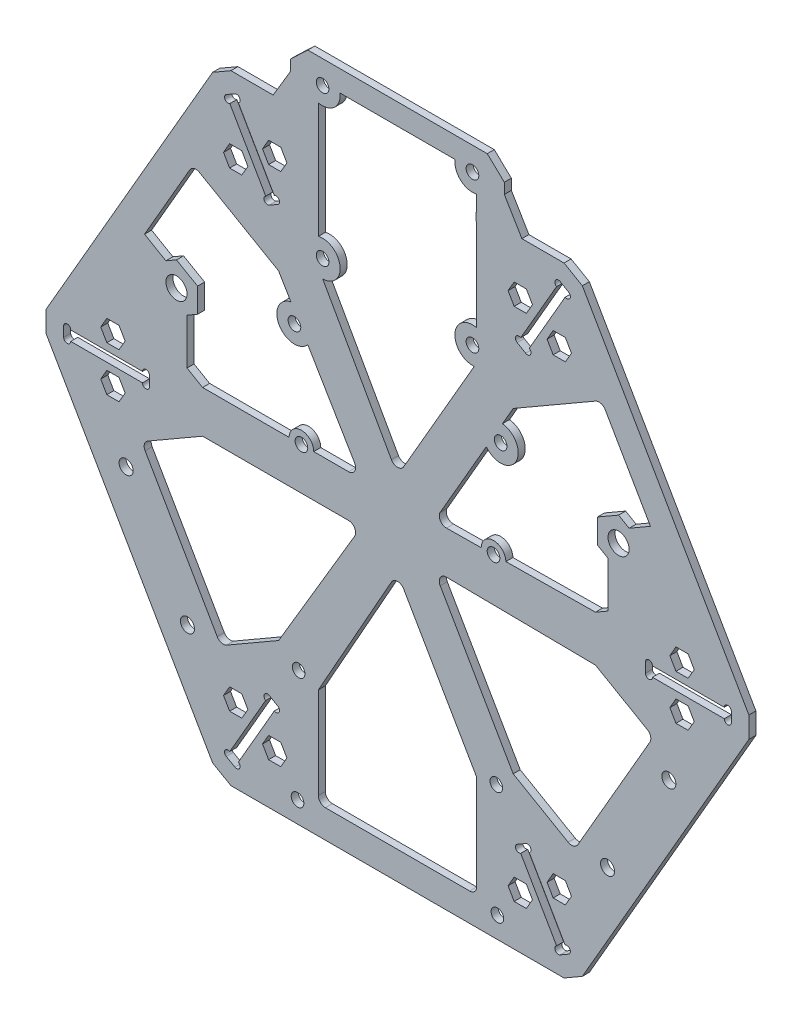
SolidWorks part; units mm, degrees
ref_plane "Alzado" through (0, 0, 0) normal (0, 0, 1) x (1, 0, 0)
ref_plane "Planta" through (0, 0, 0) normal (0, 1, 0) x (1, 0, 0)
ref_plane "Vista lateral" through (0, 0, 0) normal (1, 0, 0) x (0, 0, -1)
sketch "Croquis1" plane through (0, 0, 0) normal (0, 0, 1) x (1, 0, 0)
  line L1 (50.8068, 0) -> (25.4034, 44)
  line L2 (25.4034, 44) -> (-25.4034, 44)
  line L3 (-25.4034, 44) -> (-50.8068, 0)
  line L4 (-50.8068, 0) -> (-25.4034, -44)
  line L5 (-25.4034, -44) -> (25.4034, -44)
  line L6 (25.4034, -44) -> (50.8068, 0)
  circle A0 centre (0, 0) radius 44 construction
extrude "Saliente-Extruir1" add sketch "Croquis1" along normal blind 1
sketch "Croquis2" plane through (0, 0, 1) normal (0, 0, 1) x (1, 0, 0)
  line L0 (-25.4034, -44) -> (25.4034, -44) construction
  line L1 (-11.25, -40) -> (11.25, -40)
  line L2 (0, -44) -> (0, -40) construction
  line L3 (11.25, -40) -> (11.25, -25.4856)
  line L4 (-11.25, -40) -> (-11.25, -26)
  line L5 (0, -40) -> (0, -6) construction
  line L6 (-11.25, -26) -> (0, -6)
  line L7 (0, -6) -> (11.25, -25.4856)
  line L8 (25.4034, -44) -> (50.8068, 0) construction
  line L9 (38.1051, -22) -> (5.1962, -3) construction
  line L10 (29.016, -29.7428) -> (40.266, -10.2572)
  line L11 (29.016, -29.7428) -> (16.4462, -22.4856)
  line L12 (16.4462, -22.4856) -> (5.1962, -3)
  line L13 (5.1962, -3) -> (28.1417, -3.2572)
  line L14 (28.1417, -3.2572) -> (40.266, -10.2572)
  line L15 (-29.016, 29.7428) -> (-40.266, 10.2572)
  line L16 (-40.266, 10.2572) -> (-27.6962, 3)
  line L17 (-29.016, 29.7428) -> (-16.8917, 22.7428)
  line L18 (-16.8917, 22.7428) -> (-5.1962, 3)
  line L19 (-5.1962, 3) -> (-27.6962, 3)
  line L20 (-40.266, -10.2572) -> (-29.016, -29.7428)
  line L21 (-40.266, -10.2572) -> (-27.6962, -3)
  line L22 (-27.6962, -3) -> (-5.1962, -3)
  line L23 (-5.1962, -3) -> (-16.8917, -22.7428)
  line L24 (-16.8917, -22.7428) -> (-29.016, -29.7428)
  line L25 (-25.4034, 44) -> (-50.8068, 0) construction
  line L26 (-38.1051, 22) -> (-34.641, 20) construction
  line L27 (-34.641, 20) -> (-5.1962, 3) construction
  line L28 (-50.8068, 0) -> (-25.4034, -44) construction
  line L29 (-38.1051, -22) -> (-5.1962, -3) construction
  line L30 (40.266, 10.2572) -> (29.016, 29.7428)
  line L31 (29.016, 29.7428) -> (16.4462, 22.4856)
  line L32 (40.266, 10.2572) -> (28.1417, 3.2572)
  line L33 (28.1417, 3.2572) -> (5.1962, 3)
  line L34 (5.1962, 3) -> (16.4462, 22.4856)
  line L35 (11.25, 40) -> (-11.25, 40)
  line L36 (11.25, 40) -> (11.25, 25.4856)
  line L37 (11.25, 25.4856) -> (0, 6)
  line L38 (0, 6) -> (-11.25, 26)
  line L39 (-11.25, 26) -> (-11.25, 40)
  line L40 (50.8068, 0) -> (25.4034, 44) construction
  line L41 (38.1051, 22) -> (34.641, 20) construction
  line L42 (34.641, 20) -> (5.1962, 3) construction
  line L43 (25.4034, 44) -> (-25.4034, 44) construction
  line L44 (0, 44) -> (0, 6) construction
  arc A0 (-11.25, -39) -> (-10.25, -40) centre (-10.25, -39) ccw
  arc A1 (10.25, -40) -> (11.25, -39) centre (10.25, -39) ccw
  arc A2 (0.8773, -7.5196) -> (-0.8603, -7.5293) centre (0.0113, -8.0196) ccw
  arc A3 (6.9507, -3.0197) -> (6.0735, -4.5196) centre (6.9395, -4.0196) ccw
  arc A4 (28.15, -29.2428) -> (29.516, -28.8768) centre (28.65, -28.3768) ccw
  arc A5 (39.766, -11.1232) -> (39.4, -9.7572) centre (38.9, -10.6232) ccw
  arc A6 (-28.15, 29.2428) -> (-29.516, 28.8768) centre (-28.65, 28.3768) ccw
  arc A7 (-39.766, 11.1232) -> (-39.4, 9.7572) centre (-38.9, 10.6232) ccw
  arc A8 (-6.9508, 3) -> (-6.0905, 4.5097) centre (-6.9508, 4) ccw
  arc A9 (-6.0905, -4.5097) -> (-6.9508, -3) centre (-6.9508, -4) ccw
  arc A10 (-39.4, -9.7572) -> (-39.766, -11.1232) centre (-38.9, -10.6232) ccw
  arc A11 (-29.516, -28.8768) -> (-28.15, -29.2428) centre (-28.65, -28.3768) ccw
  arc A12 (39.4, 9.7572) -> (39.766, 11.1232) centre (38.9, 10.6232) ccw
  arc A13 (29.516, 28.8768) -> (28.15, 29.2428) centre (28.65, 28.3768) ccw
  arc A14 (6.0735, 4.5196) -> (6.9507, 3.0197) centre (6.9395, 4.0196) ccw
  arc A15 (-0.8603, 7.5293) -> (0.8773, 7.5196) centre (0.0113, 8.0196) ccw
  arc A16 (11.25, 39) -> (10.25, 40) centre (10.25, 39) ccw
  arc A17 (-10.25, 40) -> (-11.25, 39) centre (-10.25, 39) ccw
  point P7 (0, -40)
  point P20 (34.641, -20)
  point P47 (-34.641, 20)
  point P57 (-34.641, -20)
  point P83 (34.641, 20)
  point P93 (0, 40)
  point P114 (0, 0)
  dimension "D9" = 2
  dimension "D10" = 2
  dimension "D11" = 2
  dimension "D12" = 2
  dimension "D13" = 2
  dimension "D14" = 2
  dimension "D1" = 22.5
  dimension "D2" = 4
  dimension "D3" = 6
  dimension "D4" = 14
  dimension "D5" = 22.5
  dimension "D6" = 4
  dimension "D7" = 6
  dimension "D8" = 14
  dimension "D15" = 3
extrude "Cortar-Extruir2" cut sketch "Croquis2" against normal blind 1 contours L20 A11 L24 L23 A9 L22 L21 A10 | L7 A2 L6 L4 A0 L1 A1 L3 | L10 A5 L14 L13 A3 L12 L11 A4 | L34 A14 L33 L32 A12 L30 A13 L31 | L35 A17 L39 L38 A15 L37 L36 A16 | L19 A8 L18 L17 A6 L15 A7 L16
sketch "Croquis3" plane through (0, 0, 1) normal (0, 0, 1) x (1, 0, 0)
  line L0 (49.9408, -1.5) -> (49.9408, 1.5)
  line L1 (25.4034, -44) -> (50.8068, 0) construction
  line L2 (50.8068, 0) -> (25.4034, 44) construction
  line L3 (49.9408, 1.5) -> (51.6379, 1.5)
  line L4 (51.6379, 1.5) -> (51.6379, -1.5)
  line L5 (51.6379, -1.5) -> (49.9408, -1.5)
  line L6 (23.6714, -44) -> (26.2694, -42.5)
  line L7 (26.2694, -42.5) -> (27.118, -43.9697)
  line L8 (27.118, -43.9697) -> (24.5199, -45.4697)
  line L9 (24.5199, -45.4697) -> (23.6714, -44)
  line L10 (-26.2694, -42.5) -> (-23.6714, -44)
  line L11 (-23.6714, -44) -> (-24.5199, -45.4697)
  line L12 (-24.5199, -45.4697) -> (-27.118, -43.9697)
  line L13 (-27.118, -43.9697) -> (-26.2694, -42.5)
  line L14 (-49.9408, 1.5) -> (-49.9408, -1.5)
  line L15 (-49.9408, -1.5) -> (-51.6379, -1.5)
  line L16 (-51.6379, -1.5) -> (-51.6379, 1.5)
  line L17 (-51.6379, 1.5) -> (-49.9408, 1.5)
  line L18 (-23.6714, 44) -> (-26.2694, 42.5)
  line L19 (-26.2694, 42.5) -> (-27.118, 43.9697)
  line L20 (-27.118, 43.9697) -> (-24.5199, 45.4697)
  line L21 (-24.5199, 45.4697) -> (-23.6714, 44)
  line L22 (26.2694, 42.5) -> (23.6714, 44)
  line L23 (23.6714, 44) -> (24.5199, 45.4697)
  line L24 (24.5199, 45.4697) -> (27.118, 43.9697)
  line L25 (27.118, 43.9697) -> (26.2694, 42.5)
  point P31 (0, 0)
  dimension "D1" = 3
  dimension "D2" = 6
extrude "Cortar-Extruir3" cut sketch "Croquis3" against normal blind 1
sketch "Croquis4" plane through (0, 0, 1) normal (0, 0, 1) x (1, 0, 0)
  line L0 (23.7204, -41.0849) -> (17.6204, -30.5194) construction
  line L1 (24.9704, -43.25) -> (23.7204, -41.0849) construction
  line L2 (26.2694, -42.5) -> (23.6714, -44) construction
  line L3 (17.0142, -30.8694) -> (18.2266, -30.1694)
  line L4 (23.1142, -41.4349) -> (24.3266, -40.7349)
  line L5 (17.5142, -31.7355) -> (22.6142, -40.5689)
  line L6 (23.8266, -39.8689) -> (18.7266, -31.0355)
  line L7 (23.6714, -44) -> (24.9704, -43.25) construction
  line L8 (24.9704, -43.25) -> (26.2694, -42.5) construction
  line L9 (-18.2266, -30.1694) -> (-17.0142, -30.8694)
  line L10 (-24.3266, -40.7349) -> (-23.1142, -41.4349)
  line L11 (-18.7266, -31.0355) -> (-23.8266, -39.8689)
  line L12 (-22.6142, -40.5689) -> (-17.5142, -31.7355)
  line L13 (-23.7204, -41.0849) -> (-17.6204, -30.5194) construction
  line L14 (-24.9704, -43.25) -> (-23.7204, -41.0849) construction
  line L15 (-26.2694, -42.5) -> (-24.9704, -43.25) construction
  line L16 (-24.9704, -43.25) -> (-23.6714, -44) construction
  line L17 (-35.2408, 0.7) -> (-35.2408, -0.7)
  line L18 (-47.4408, 0.7) -> (-47.4408, -0.7)
  line L19 (-36.2408, 0.7) -> (-46.4408, 0.7)
  line L20 (-46.4408, -0.7) -> (-36.2408, -0.7)
  line L21 (-47.4408, 0) -> (-35.2408, 0) construction
  line L22 (-49.9408, 0) -> (-47.4408, 0) construction
  line L23 (-49.9408, 1.5) -> (-49.9408, 0) construction
  line L24 (-49.9408, 0) -> (-49.9408, -1.5) construction
  line L25 (-17.0142, 30.8694) -> (-18.2266, 30.1694)
  line L26 (-23.1142, 41.4349) -> (-24.3266, 40.7349)
  line L27 (-17.5142, 31.7355) -> (-22.6142, 40.5689)
  line L28 (-23.8266, 39.8689) -> (-18.7266, 31.0355)
  line L29 (-23.7204, 41.0849) -> (-17.6204, 30.5194) construction
  line L30 (-24.9704, 43.25) -> (-23.7204, 41.0849) construction
  line L31 (-23.6714, 44) -> (-24.9704, 43.25) construction
  line L32 (-24.9704, 43.25) -> (-26.2694, 42.5) construction
  line L33 (18.2266, 30.1694) -> (17.0142, 30.8694)
  line L34 (24.3266, 40.7349) -> (23.1142, 41.4349)
  line L35 (18.7266, 31.0355) -> (23.8266, 39.8689)
  line L36 (22.6142, 40.5689) -> (17.5142, 31.7355)
  line L37 (23.7204, 41.0849) -> (17.6204, 30.5194) construction
  line L38 (24.9704, 43.25) -> (23.7204, 41.0849) construction
  line L39 (26.2694, 42.5) -> (24.9704, 43.25) construction
  line L40 (24.9704, 43.25) -> (23.6714, 44) construction
  line L41 (35.2408, -0.7) -> (35.2408, 0.7)
  line L42 (47.4408, -0.7) -> (47.4408, 0.7)
  line L43 (36.2408, -0.7) -> (46.4408, -0.7)
  line L44 (46.4408, 0.7) -> (36.2408, 0.7)
  line L45 (47.4408, 0) -> (35.2408, 0) construction
  line L46 (49.9408, 0) -> (47.4408, 0) construction
  line L47 (49.9408, -1.5) -> (49.9408, 0) construction
  line L48 (49.9408, 0) -> (49.9408, 1.5) construction
  line L49 (-15.7171, -36.6228) -> (-16.5831, -35.1228)
  line L50 (19.1812, -36.6228) -> (18.3151, -35.1228)
  line L51 (18.3151, -35.1228) -> (16.5831, -35.1228)
  line L52 (16.5831, -35.1228) -> (15.7171, -36.6228)
  line L53 (15.7171, -36.6228) -> (16.5831, -38.1228)
  line L54 (16.5831, -38.1228) -> (18.3151, -38.1228)
  line L55 (18.3151, -38.1228) -> (19.1812, -36.6228)
  line L56 (23.8577, -31.9228) -> (22.1257, -31.9228)
  line L57 (22.1257, -31.9228) -> (21.2596, -33.4228)
  line L58 (21.2596, -33.4228) -> (22.1257, -34.9228)
  line L59 (22.1257, -34.9228) -> (23.8577, -34.9228)
  line L60 (23.8577, -34.9228) -> (24.7237, -33.4228)
  line L61 (24.7237, -33.4228) -> (23.8577, -31.9228)
  line L62 (-16.5831, -35.1228) -> (-18.3151, -35.1228)
  line L63 (-18.3151, -35.1228) -> (-19.1812, -36.6228)
  line L64 (-19.1812, -36.6228) -> (-18.3151, -38.1228)
  line L65 (-18.3151, -38.1228) -> (-16.5831, -38.1228)
  line L66 (-16.5831, -38.1228) -> (-15.7171, -36.6228)
  line L67 (-22.1257, -34.9228) -> (-21.2596, -33.4228)
  line L68 (-21.2596, -33.4228) -> (-22.1257, -31.9228)
  line L69 (-22.1257, -31.9228) -> (-23.8577, -31.9228)
  line L70 (-23.8577, -31.9228) -> (-24.7237, -33.4228)
  line L71 (-24.7237, -33.4228) -> (-23.8577, -34.9228)
  line L72 (-23.8577, -34.9228) -> (-22.1257, -34.9228)
  line L73 (-39.5748, -4.7) -> (-38.7087, -3.2)
  line L74 (-38.7087, -3.2) -> (-39.5748, -1.7)
  line L75 (-39.5748, -1.7) -> (-41.3068, -1.7)
  line L76 (-41.3068, -1.7) -> (-42.1728, -3.2)
  line L77 (-42.1728, -3.2) -> (-41.3068, -4.7)
  line L78 (-41.3068, -4.7) -> (-39.5748, -4.7)
  line L79 (-41.3068, 1.7) -> (-39.5748, 1.7)
  line L80 (-39.5748, 1.7) -> (-38.7087, 3.2)
  line L81 (-38.7087, 3.2) -> (-39.5748, 4.7)
  line L82 (-39.5748, 4.7) -> (-41.3068, 4.7)
  line L83 (-41.3068, 4.7) -> (-42.1728, 3.2)
  line L84 (-42.1728, 3.2) -> (-41.3068, 1.7)
  line L85 (-23.8577, 31.9228) -> (-22.1257, 31.9228)
  line L86 (-22.1257, 31.9228) -> (-21.2596, 33.4228)
  line L87 (-21.2596, 33.4228) -> (-22.1257, 34.9228)
  line L88 (-22.1257, 34.9228) -> (-23.8577, 34.9228)
  line L89 (-23.8577, 34.9228) -> (-24.7237, 33.4228)
  line L90 (-24.7237, 33.4228) -> (-23.8577, 31.9228)
  line L91 (-19.1812, 36.6228) -> (-18.3151, 35.1228)
  line L92 (-18.3151, 35.1228) -> (-16.5831, 35.1228)
  line L93 (-16.5831, 35.1228) -> (-15.7171, 36.6228)
  line L94 (-15.7171, 36.6228) -> (-16.5831, 38.1228)
  line L95 (-16.5831, 38.1228) -> (-18.3151, 38.1228)
  line L96 (-18.3151, 38.1228) -> (-19.1812, 36.6228)
  line L97 (15.7171, 36.6228) -> (16.5831, 35.1228)
  line L98 (16.5831, 35.1228) -> (18.3151, 35.1228)
  line L99 (18.3151, 35.1228) -> (19.1812, 36.6228)
  line L100 (19.1812, 36.6228) -> (18.3151, 38.1228)
  line L101 (18.3151, 38.1228) -> (16.5831, 38.1228)
  line L102 (16.5831, 38.1228) -> (15.7171, 36.6228)
  line L103 (22.1257, 34.9228) -> (21.2596, 33.4228)
  line L104 (21.2596, 33.4228) -> (22.1257, 31.9228)
  line L105 (22.1257, 31.9228) -> (23.8577, 31.9228)
  line L106 (23.8577, 31.9228) -> (24.7237, 33.4228)
  line L107 (24.7237, 33.4228) -> (23.8577, 34.9228)
  line L108 (23.8577, 34.9228) -> (22.1257, 34.9228)
  line L109 (39.5748, 4.7) -> (38.7087, 3.2)
  line L110 (38.7087, 3.2) -> (39.5748, 1.7)
  line L111 (39.5748, 1.7) -> (41.3068, 1.7)
  line L112 (41.3068, 1.7) -> (42.1728, 3.2)
  line L113 (42.1728, 3.2) -> (41.3068, 4.7)
  line L114 (41.3068, 4.7) -> (39.5748, 4.7)
  line L115 (41.3068, -1.7) -> (39.5748, -1.7)
  line L116 (39.5748, -1.7) -> (38.7087, -3.2)
  line L117 (38.7087, -3.2) -> (39.5748, -4.7)
  line L118 (39.5748, -4.7) -> (41.3068, -4.7)
  line L119 (41.3068, -4.7) -> (42.1728, -3.2)
  line L120 (42.1728, -3.2) -> (41.3068, -1.7)
  arc A0 (18.7266, -31.0355) -> (18.2266, -30.1694) centre (18.4766, -30.6024) ccw
  arc A1 (17.0142, -30.8694) -> (17.5142, -31.7355) centre (17.2642, -31.3024) ccw
  arc A2 (22.6142, -40.5689) -> (23.1142, -41.4349) centre (22.8642, -41.0019) ccw
  arc A3 (24.3266, -40.7349) -> (23.8266, -39.8689) centre (24.0766, -40.3019) ccw
  arc A4 (-17.5142, -31.7355) -> (-17.0142, -30.8694) centre (-17.2642, -31.3024) ccw
  arc A5 (-18.2266, -30.1694) -> (-18.7266, -31.0355) centre (-18.4766, -30.6024) ccw
  arc A6 (-23.8266, -39.8689) -> (-24.3266, -40.7349) centre (-24.0766, -40.3019) ccw
  arc A7 (-23.1142, -41.4349) -> (-22.6142, -40.5689) centre (-22.8642, -41.0019) ccw
  arc A8 (-36.2408, -0.7) -> (-35.2408, -0.7) centre (-35.7408, -0.7) ccw
  arc A9 (-35.2408, 0.7) -> (-36.2408, 0.7) centre (-35.7408, 0.7) ccw
  arc A10 (-46.4408, 0.7) -> (-47.4408, 0.7) centre (-46.9408, 0.7) ccw
  arc A11 (-47.4408, -0.7) -> (-46.4408, -0.7) centre (-46.9408, -0.7) ccw
  arc A12 (-18.7266, 31.0355) -> (-18.2266, 30.1694) centre (-18.4766, 30.6024) ccw
  arc A13 (-17.0142, 30.8694) -> (-17.5142, 31.7355) centre (-17.2642, 31.3024) ccw
  arc A14 (-22.6142, 40.5689) -> (-23.1142, 41.4349) centre (-22.8642, 41.0019) ccw
  arc A15 (-24.3266, 40.7349) -> (-23.8266, 39.8689) centre (-24.0766, 40.3019) ccw
  arc A16 (17.5142, 31.7355) -> (17.0142, 30.8694) centre (17.2642, 31.3024) ccw
  arc A17 (18.2266, 30.1694) -> (18.7266, 31.0355) centre (18.4766, 30.6024) ccw
  arc A18 (23.8266, 39.8689) -> (24.3266, 40.7349) centre (24.0766, 40.3019) ccw
  arc A19 (23.1142, 41.4349) -> (22.6142, 40.5689) centre (22.8642, 41.0019) ccw
  arc A20 (36.2408, 0.7) -> (35.2408, 0.7) centre (35.7408, 0.7) ccw
  arc A21 (35.2408, -0.7) -> (36.2408, -0.7) centre (35.7408, -0.7) ccw
  arc A22 (46.4408, -0.7) -> (47.4408, -0.7) centre (46.9408, -0.7) ccw
  arc A23 (47.4408, 0.7) -> (46.4408, 0.7) centre (46.9408, 0.7) ccw
  circle A24 centre (17.4491, -36.6228) radius 1.5 construction
  circle A25 centre (22.9917, -33.4228) radius 1.5 construction
  point P8 (17.6204, -30.5194)
  point P11 (23.7204, -41.0849)
  point P32 (-17.6204, -30.5194)
  point P35 (-23.7204, -41.0849)
  point P51 (-35.2408, 0)
  point P54 (-47.4408, 0)
  point P70 (-17.6204, 30.5194)
  point P73 (-23.7204, 41.0849)
  point P89 (17.6204, 30.5194)
  point P92 (23.7204, 41.0849)
  point P108 (35.2408, 0)
  point P111 (47.4408, 0)
  point P121 (0, 0)
  point P128 (21.6926, -34.1728)
  point P199 (0, 0)
  dimension "D4" = 1
  dimension "D5" = 1
  dimension "D6" = 1
  dimension "D7" = 1
  dimension "D9" = 3
  dimension "D10" = 3
  dimension "D1" = 2.5
  dimension "D2" = 12.2
  dimension "D3" = 1.4
  dimension "D8" = 6
  dimension "D11" = 1
  dimension "D12" = 1
  dimension "D13" = 9.5
  dimension "D14" = 9.5
  dimension "D15" = 6
extrude "Cortar-Extruir4" cut sketch "Croquis4" against normal blind 1
sketch "Croquis5" plane through (0, 0, 1) normal (0, 0, 1) x (1, 0, 0)
  line L0 (0, -44) -> (0, -23.6634) construction
  line L1 (-23.6714, -44) -> (23.6714, -44) construction
  line L2 (-22.6142, -40.5689) -> (-17.5142, -31.7355) construction
  circle A0 centre (-14.2028, -41) radius 0.9
  circle A1 centre (-14.05, -25) radius 0.9
  circle A2 centre (14.05, -25) radius 0.9
  circle A3 centre (14.2028, -41) radius 0.9
  dimension "D1" = 1.8
  dimension "D3" = 7.5
  dimension "D4" = 1.8
  dimension "D6" = 19
  dimension "D2" = 3
  dimension "D5" = 2.8
extrude "Cortar-Extruir5" cut sketch "Croquis5" against normal blind 1
sketch "Croquis7" plane through (0, 0, 1) normal (0, 0, 1) x (1, 0, 0)
  line L0 (25.1189, -27.4928) -> (36.3689, -8.0072)
  line L1 (28.15, -29.2428) -> (16.4462, -22.4856) construction
  line L2 (28.1417, -3.2572) -> (39.4, -9.7572) construction
  line L3 (26.2694, -42.5) -> (49.9408, -1.5) construction
  line L4 (0, -44) -> (0, 0) construction
  line L6 (32.4801, -31.7428) -> (43.7301, -12.2572)
  line L7 (43.7301, -12.2572) -> (36.3689, -8.0072)
  line L8 (25.1189, -27.4928) -> (32.4801, -31.7428)
  line L9 (25.1189, -27.4928) -> (24.2529, -26.9928)
  line L10 (36.3689, -8.0072) -> (35.5029, -7.5072)
  line L11 (-36.3689, -8.0072) -> (-35.5029, -7.5072)
  line L12 (-25.1189, -27.4928) -> (-24.2529, -26.9928)
  line L13 (-25.1189, -27.4928) -> (-32.4801, -31.7428)
  line L14 (-43.7301, -12.2572) -> (-36.3689, -8.0072)
  line L15 (-32.4801, -31.7428) -> (-43.7301, -12.2572)
  line L16 (-25.1189, -27.4928) -> (-36.3689, -8.0072)
  line L17 (-23.6714, -44) -> (23.6714, -44) construction
  circle A2 centre (24.7529, -26.1268) radius 1
  circle A3 centre (35.0029, -8.3732) radius 1
  circle A4 centre (-35.0029, -8.3732) radius 1
  circle A5 centre (-24.7529, -26.1268) radius 1
  point P16 (38.1051, -22)
  point P33 (-38.1051, -22)
  dimension "D1" = 8.5
  dimension "D2" = 1
  dimension "D3" = 1
extrude "Saliente-Extruir2" add sketch "Croquis7" against normal blind 1 contours L0 L8 L6 L7 | A2 L9 L0 | A3 L0 L10 | L13 L16 L14 L15 | L16 A4 L11 | L12 A5 L16
sketch "Croquis8" plane through (0, 0, 1) normal (0, 0, 1) x (1, 0, 0)
  line L0 (0, -44) -> (0, 0) construction
  line L1 (-23.6714, -44) -> (23.6714, -44) construction
  line L2 (0, 0) -> (38.1051, -22) construction
  line L3 (26.2694, -42.5) -> (49.9408, -1.5) construction
  line L4 (23.8266, -39.8689) -> (18.7266, -31.0355) construction
  circle A0 centre (29.849, -27.3) radius 1
  circle A1 centre (38.567, -12.2) radius 1
  circle A2 centre (29.849, -27.3) radius 1
  circle A3 centre (38.567, -12.2) radius 1
  circle A4 centre (-38.567, -12.2) radius 1
  circle A5 centre (-38.567, -12.2) radius 1
  circle A6 centre (-29.849, -27.3) radius 1
  circle A7 centre (-29.849, -27.3) radius 1
  dimension "D1" = 2
  dimension "D2" = 4.5
  dimension "D3" = 11.5
extrude "Cortar-Extruir6" cut sketch "Croquis8" against normal blind 1 contours A1 | A6 | A4 | A0
sketch "Croquis9" plane through (0, 0, 1) normal (0, 0, 1) x (1, 0, 0)
  line L0 (-13.65, 0) -> (13.65, 0) construction
  line L1 (-13.65, 0) -> (-13.65, 3) construction
  line L2 (-6.9508, 3) -> (-27.6962, 3) construction
  line L3 (13.65, 0) -> (13.65, 3.0948) construction
  line L4 (28.1417, 3.2572) -> (6.9507, 3.0197) construction
  circle A0 centre (-13.65, 3) radius 1.75
  circle A1 centre (13.65, 3.0948) radius 1.75
  point P4 (0, 0)
  dimension "D1" = 3.5
  dimension "D2" = 3.5
extrude "Saliente-Extruir3" add sketch "Croquis9" against normal blind 1
sketch "Croquis10" plane through (0, 0, 1) normal (0, 0, 1) x (1, 0, 0)
  line L0 (-13.65, 0) -> (13.65, 0) construction
  line L1 (-13.65, 0) -> (-13.65, 3) construction
  line L2 (13.65, 0) -> (13.65, 3.0948) construction
  circle A0 centre (-13.65, 3) radius 0.9
  circle A1 centre (13.65, 3.0948) radius 0.9
  point P4 (0, 0)
  point P10 (13.65, 3.0948)
  dimension "D1" = 1.8
  dimension "D2" = 1.8
extrude "Cortar-Extruir7" cut sketch "Croquis10" against normal blind 1
sketch "Croquis11" plane through (0, 0, 1) normal (0, 0, 1) x (1, 0, 0)
  line L0 (29.9203, 10.7841) -> (29.9203, 4.2841)
  line L1 (34.4203, 11.6502) -> (34.4203, 15.1143)
  line L2 (34.4203, 15.1143) -> (31.4203, 16.8463)
  line L3 (31.4203, 16.8463) -> (28.4203, 15.1143)
  line L4 (28.4203, 15.1143) -> (28.4203, 11.6502)
  line L5 (28.4203, 11.6502) -> (31.4203, 9.9181)
  line L6 (31.4203, 9.9181) -> (34.4203, 11.6502)
  line L7 (34.641, 20) -> (38.7727, 12.8437) construction
  line L8 (39.766, 11.1232) -> (29.516, 28.8768) construction
  line L9 (32.9203, 15.9803) -> (35.9514, 17.7303)
  line L10 (28.1417, 3.2572) -> (39.4, 9.7572) construction
  line L11 (39.4, 9.7572) -> (28.1417, 3.2572) construction
  line L12 (39.4, 9.7572) -> (40.266, 10.2572) construction
  line L13 (40.266, 10.2572) -> (38.7727, 12.8437) construction
  line L14 (0.0057, -7.0196) -> (0.0057, 7.0196) construction
  line L15 (-40.2546, 10.2572) -> (-38.7613, 12.8437) construction
  line L16 (-39.3886, 9.7572) -> (-40.2546, 10.2572) construction
  line L17 (-28.1302, 3.2572) -> (-39.3886, 9.7572) construction
  line L18 (-34.6296, 20) -> (-38.7613, 12.8437) construction
  line L19 (-37.2793, 18.4881) -> (-35.94, 17.7303)
  line L26 (-41.9378, 9.7572) -> (-37.2793, 18.4881)
  line L27 (29.9203, 4.2841) -> (30.5366, 3.6679)
  line L28 (30.5366, 3.6679) -> (41.9492, 9.7572)
  line L29 (41.9492, 9.7572) -> (37.2907, 18.4881)
  line L30 (37.2907, 18.4881) -> (35.9514, 17.7303)
  line L31 (-30.5252, 3.6679) -> (-41.9378, 9.7572)
  line L32 (-29.9089, 4.2841) -> (-30.5252, 3.6679)
  line L33 (-32.9089, 15.9803) -> (-35.94, 17.7303)
  line L34 (-31.4089, 9.9181) -> (-34.4089, 11.6502)
  line L35 (-28.4089, 11.6502) -> (-31.4089, 9.9181)
  line L36 (-28.4089, 15.1143) -> (-28.4089, 11.6502)
  line L37 (-31.4089, 16.8463) -> (-28.4089, 15.1143)
  line L38 (-34.4089, 15.1143) -> (-31.4089, 16.8463)
  line L39 (-34.4089, 11.6502) -> (-34.4089, 15.1143)
  line L40 (-29.9089, 10.7841) -> (-29.9089, 4.2841)
  circle A0 centre (31.4203, 13.3822) radius 3 construction
  arc A1 (39.4, 9.7572) -> (39.766, 11.1232) centre (38.9, 10.6232) ccw construction
  circle A2 centre (31.4203, 13.3822) radius 1.5
  arc A3 (0.8773, -7.5196) -> (-0.8603, -7.5293) centre (0.0113, -8.0196) ccw construction
  arc A4 (-0.8603, 7.5293) -> (0.8773, 7.5196) centre (0.0113, 8.0196) ccw construction
  circle A7 centre (-31.4089, 13.3822) radius 3 construction
  circle A8 centre (-31.4089, 13.3822) radius 1.5
  dimension "D1" = 6
  dimension "D4" = 3
  dimension "D2" = 6.5
  dimension "D3" = 3.5
extrude "Saliente-Extruir4" add sketch "Croquis11" against normal blind 1
sketch "Croquis12" plane through (0, 0, 1) normal (0, 0, 1) x (1, 0, 0)
  line L0 (0.0057, -7.0196) -> (0.0057, 7.0196) construction
  line L1 (0.0057, 7.0196) -> (0.0057, 52.7352) construction
  line L2 (10.6557, 27.3913) -> (0.0057, 27.3913) construction
  line L3 (0.0057, 27.3913) -> (-10.6443, 27.3913) construction
  line L4 (14.6557, 17.3594) -> (0.0057, 17.3594) construction
  line L5 (0.0057, 17.3594) -> (-14.6443, 17.3594) construction
  line L6 (10.6557, 27.3913) -> (14.6557, 17.3594) construction
  line L7 (14.6557, 17.3594) -> (13.65, 3.0948) construction
  circle A0 centre (-14.6443, 17.3594) radius 2.5
  circle A1 centre (-10.6443, 27.3913) radius 2.5
  circle A2 centre (10.6557, 27.3913) radius 2.5
  circle A3 centre (14.6557, 17.3594) radius 2.5
  arc A4 (0.8773, -7.5196) -> (-0.8603, -7.5293) centre (0.0113, -8.0196) ccw construction
  arc A5 (-0.8603, 7.5293) -> (0.8773, 7.5196) centre (0.0113, 8.0196) ccw construction
  point P18 (15.1262, 17.3184)
  point P20 (10.6557, 27.3913)
  dimension "D1" = 5
  dimension "D2" = 5
  dimension "D3" = 5
  dimension "D4" = 5
  dimension "D5" = 21.3
  dimension "D6" = 10.8
  dimension "D7" = 14.3
  dimension "D8" = 29.3
extrude "Saliente-Extruir5" add sketch "Croquis12" against normal blind 1
sketch "Croquis13" plane through (0, 0, 1) normal (0, 0, 1) x (1, 0, 0)
  circle A0 centre (14.6557, 17.3594) radius 0.9
  circle A1 centre (10.6557, 27.3913) radius 0.9
  circle A2 centre (-10.6443, 27.3913) radius 0.9
  circle A3 centre (-14.6443, 17.3594) radius 0.9
  dimension "D1" = 1.8
  dimension "D2" = 1.8
  dimension "D3" = 1.8
  dimension "D4" = 1.8
extrude "Cortar-Extruir8" cut sketch "Croquis13" against normal blind 1
sketch "Croquis14" plane through (0, 0, 1) normal (0, 0, 1) x (1, 0, 0)
  line L0 (-11.25, 39) -> (-11.25, 44)
  line L1 (23.6714, 44) -> (-23.6714, 44) construction
  line L2 (-11.25, 44) -> (11.1783, 44)
  line L3 (11.1783, 44) -> (11.25, 39)
  line L4 (11.25, 39) -> (-11.25, 39)
extrude "Cortar-Extruir9" cut sketch "Croquis14" against normal blind 1
sketch "Croquis15" plane through (0, 0, 1) normal (0, 0, 1) x (1, 0, 0)
  line L0 (0.0057, -7.0196) -> (0.0057, 7.0196) construction
  line L1 (0.0057, 7.0196) -> (0.0057, 65.5541) construction
  line L2 (-12.7443, 52) -> (12.7557, 52)
  line L6 (-23.6714, 44) -> (23.6714, 44) construction
  line L7 (-12.7443, 52) -> (-15.1714, 49.7)
  line L8 (-15.1714, 49.7) -> (-15.1714, 48.2)
  line L9 (-15.1714, 48.2) -> (-17.6714, 44)
  line L10 (-11.25, 44) -> (-11.25, 49)
  line L11 (-11.25, 49) -> (11.2614, 49)
  line L12 (11.2614, 44) -> (11.2614, 49)
  line L13 (15.1828, 48.2) -> (17.6828, 44)
  line L14 (15.1828, 49.7) -> (15.1828, 48.2)
  line L15 (12.7557, 52) -> (15.1828, 49.7)
  line L16 (-17.6714, 44) -> (-11.25, 44)
  line L17 (11.2614, 44) -> (17.6828, 44)
  arc A0 (0.8773, -7.5196) -> (-0.8603, -7.5293) centre (0.0113, -8.0196) ccw construction
  arc A1 (-0.8603, 7.5293) -> (0.8773, 7.5196) centre (0.0113, 8.0196) ccw construction
  point P12 (0.0057, 52)
  point P22 (0.0057, 49)
  point P24 (0.0057, 49)
  dimension "D1" = 8
  dimension "D2" = 25.5
  dimension "D3" = 6
  dimension "D4" = 2.5
  dimension "D5" = 1.5
  dimension "D6" = 4.2
  dimension "D7" = 3
extrude "Saliente-Extruir6" add sketch "Croquis15" against normal blind 1 contours L11 L12 L17 L13 L14 L15 L2 L7 L8 L9 L16 L10
sketch "Croquis16" plane through (0, 0, 0) normal (0, 0, -1) x (-1, 0, 0)
  line L0 (-10.6557, 27.3913) -> (-10.6557, 48.6913) construction
  line L1 (-0.0057, 49) -> (-0.0057, 24.8845) construction
  line L2 (11.25, 49) -> (-11.2614, 49) construction
  line L3 (10.6443, 27.3913) -> (10.6443, 48.6913) construction
  circle A1 centre (-10.6557, 48.6913) radius 2.5
  circle A4 centre (10.6443, 48.6913) radius 2.5
  dimension "D1" = 5
  dimension "D2" = 21.3
extrude "Saliente-Extruir7" add sketch "Croquis16" against normal blind 1
sketch "Croquis17" plane through (0, 0, 0) normal (0, 0, -1) x (-1, 0, 0)
  circle A0 centre (-10.6557, 48.6913) radius 0.9
  circle A1 centre (10.6443, 48.6913) radius 0.9
  dimension "D1" = 1.8
  dimension "D2" = 1.8
extrude "Cortar-Extruir10" cut sketch "Croquis17" against normal blind 1
